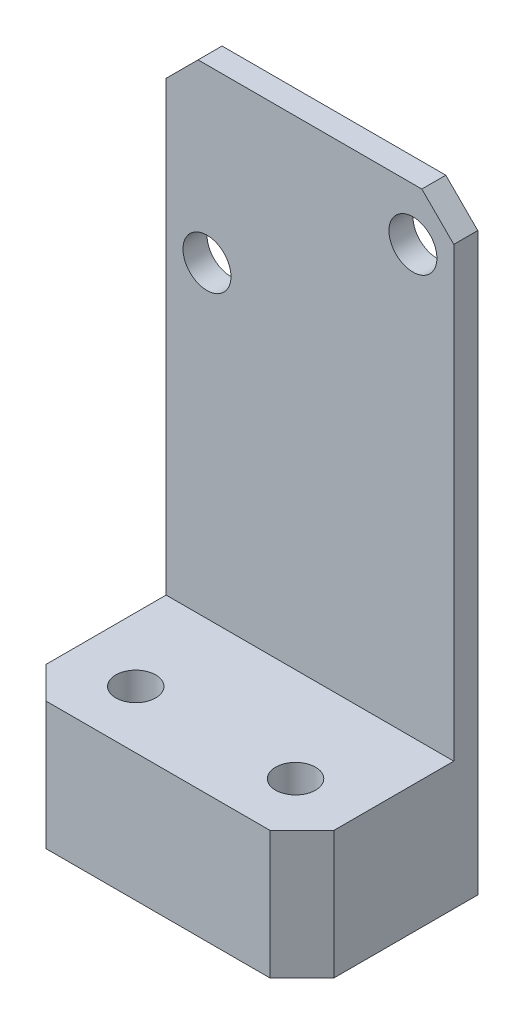
SolidWorks part; units mm, degrees
ref_plane "Front" through (0, 0, 0) normal (0, 0, 1) x (1, 0, 0)
ref_plane "Top" through (0, 0, 0) normal (0, 1, 0) x (1, 0, 0)
ref_plane "Right" through (0, 0, 0) normal (1, 0, 0) x (0, 0, -1)
sketch "Sketch1" plane through (0, 0, 0) normal (0, 0, 1) x (1, 0, 0)
  line L1 (-9, 7) -> (9, 7)
  line L2 (-9, 7) -> (-9, -31)
  line L3 (-9, -31) -> (9, -31)
  line L4 (9, 7) -> (9, -31)
  dimension "D1" = 9
  dimension "D2" = 9
  dimension "D3" = 7
  dimension "D4" = 31
extrude "Extrude1" add sketch "Sketch1" along normal blind 11
sketch "Sketch2" plane through (0, 0, 11) normal (0, 0, 1) x (1, 0, 0)
  line L0 (9, -31) -> (9, 7) construction
  line L1 (-9, 7) -> (9, 7)
  line L2 (-9, 7) -> (-9, -23)
  line L3 (-9, -23) -> (9, -23)
  line L4 (9, 7) -> (9, -23)
  line L5 (-9, -31) -> (9, -31) construction
  dimension "D1" = 8
extrude "Extrude2" cut sketch "Sketch2" against normal blind 9.5
sketch "Sketch3" plane through (0, 0, 1.5) normal (0, 0, 1) x (1, 0, 0)
  circle A0 centre (6.4432, 3.72) radius 1.5
  circle A1 centre (-6.4432, -3.72) radius 1.5
  dimension "D5" = 3
  dimension "D6" = 3
  dimension "D1" = 7.44
  dimension "D2" = 7.44
  dimension "D3" = 3.72
  dimension "D4" = 3.72
extrude "Extrude3" cut sketch "Sketch3" against normal up to surface (1.5 mm away) up to face at (0, -12, 0)
sketch "Sketch4" plane through (0, -23, 0) normal (0, 1, 0) x (1, 0, 0)
  line L1 (-9, -1.5) -> (-9, -11) construction
  line L2 (9, -1.5) -> (9, -11) construction
  line L3 (-9, -1.5) -> (9, -1.5) construction
  circle A0 centre (-5, -7.4) radius 1.25
  circle A1 centre (5, -7.4) radius 1.25
  dimension "D3" = 2.5
  dimension "D4" = 2.5
  dimension "D1" = 5.9
  dimension "D2" = 5.9
  dimension "D5" = 4
  dimension "D6" = 4
extrude "Extrude5" cut sketch "Sketch4" against normal up to surface (8 mm away) up to face at (0, -31, 5.5)
cosmetic thread "Hole Thread7" parameters "D1"=8, "D2"=3
cosmetic thread "Hole Thread8" parameters "D1"=8, "D2"=3
hole_wizard "M3 Tapped Hole3" positions "3DSketch3" profile "Sketch7" tap size "M3" standard "DIN"
sketch3d "3DSketch3"
  line L0 (5, -31, 7.4) -> (5, -23, 7.4) construction
  line L1 (-5, -31, 7.4) -> (-5, -23, 7.4) construction
  point P0 (5, -31, 7.4)
  point P4 (-5, -31, 7.4)
sketch "Sketch7" plane through (5, -31, 7.4) normal (1, 0, 0) x (0, 0, -1)
  line L0 (0, 0) -> (0, 12.2511)
  line L1 (0, 12.2511) -> (1.25, 11.5)
  line L2 (1.25, 11.5) -> (1.25, 0)
  line L5 (1.25, 0) -> (0, 0)
  line L10 (0, 12.2511) -> (-1.25, 11.5) construction
  line L11 (0, -6.35) -> (0, 107.95) construction
  dimension "Tap Drill Dia." = 2.5
  dimension "Tap Drill Depth" = 11.5
  dimension "Drill Angle" = 118
chamfer "Chamfer2" distance 2 angle 45 4 edges at (9, 7, 0.75) (-9, 7, 0.75) (-9, -27, 11) (9, -27, 11)
